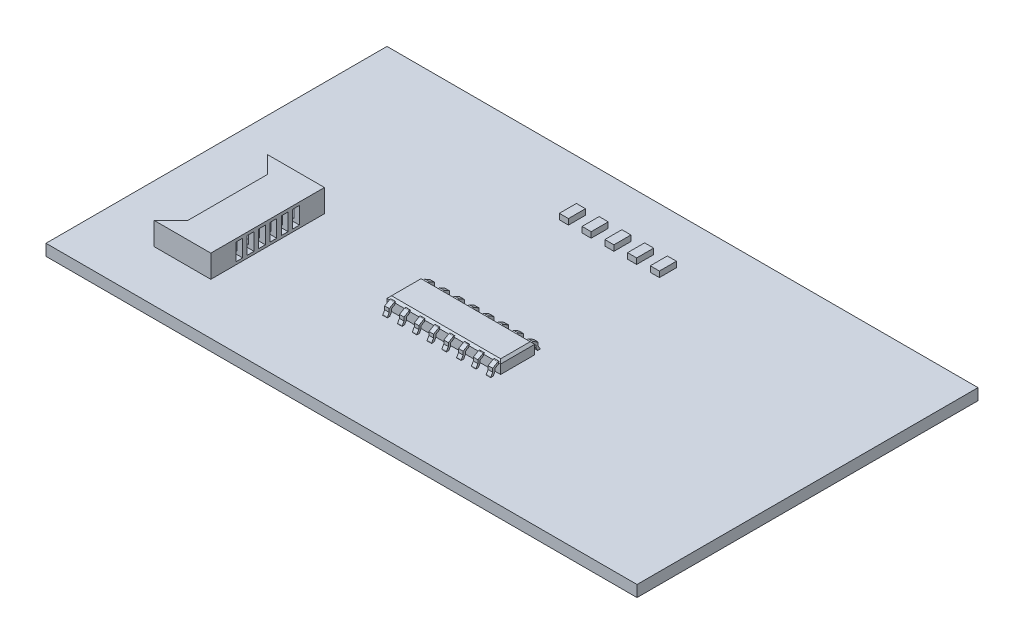
SolidWorks part; units mm, degrees
ref_plane "前视基准面" through (0, 0, 0) normal (0, 0, 1) x (1, 0, 0)
ref_plane "上视基准面" through (0, 0, 0) normal (0, 1, 0) x (1, 0, 0)
ref_plane "右视基准面" through (0, 0, 0) normal (1, 0, 0) x (0, 0, -1)
sketch "草图1" plane through (0, 0, 0) normal (0, 1, 0) x (1, 0, 0)
  line L1 (0, 0) -> (52, 0)
  line L2 (0, 0) -> (0, 30)
  line L3 (0, 30) -> (52, 30)
  line L4 (52, 0) -> (52, 30)
  dimension "D1" = 52
  dimension "D2" = 30
extrude "凸台-拉伸1" add sketch "草图1" along normal blind 1
sketch "草图2" plane through (0, 1, 0) normal (0, 1, 0) x (1, 0, 0)
  line L0 (0, 0) -> (52, 0) construction
  line L1 (5, 4.5) -> (10, 4.5)
  line L2 (5, 4.5) -> (5, 14.5)
  line L3 (5, 14.5) -> (10, 14.5)
  line L4 (10, 4.5) -> (10, 14.5)
  line L5 (0, 30) -> (0, 0) construction
  dimension "D1" = 5
  dimension "D2" = 10
  dimension "D3" = 14.5
  dimension "D4" = 5
extrude "凸台-拉伸2" add sketch "草图2" along normal blind 2
sketch "草图3" plane through (0, 3, 0) normal (0, 1, 0) x (1, 0, 0)
  line L0 (5, 14.5) -> (6.5, 13)
  line L1 (6.5, 13) -> (6.5, 6)
  line L2 (6.5, 6) -> (5, 4.5)
  line L3 (5, 4.5) -> (5, 14.5)
  dimension "D1" = 45
  dimension "D2" = 45
  dimension "D3" = 1.5
sketch "草图4" plane through (5, 0, 0) normal (-1, 0, 0) x (0, 0, 1)
  line L0 (-14.5, 2) -> (-4.5, 2) construction
  line L1 (-13.5, 1.5) -> (-5.5, 1.5)
  line L2 (-13.5, 1.5) -> (-13.5, 2.5)
  line L3 (-13.5, 2.5) -> (-5.5, 2.5)
  line L4 (-5.5, 1.5) -> (-5.5, 2.5)
  line L5 (-13.5, 1.5) -> (-5.5, 2.5) construction
  line L6 (-13.5, 2.5) -> (-5.5, 1.5) construction
  line L7 (-14.5, 3) -> (-14.5, 1) construction
  line L8 (-4.5, 3) -> (-4.5, 1) construction
  line L9 (-9.5, 3) -> (-9.5, 1) construction
  line L10 (-13, 3) -> (-6, 3) construction
  line L11 (-14.5, 1) -> (-4.5, 1) construction
  point P0 (-9.5, 2)
  point P18 (-9.5, 2)
  dimension "D1" = 8
  dimension "D2" = 1
extrude "切除-拉伸1" cut sketch "草图4" against normal blind 4.5
extrude "切除-拉伸2" cut sketch "草图3" against normal blind 1.5 contours L1 L2 L3 L0
sketch "草图5" plane through (5, 0, 0) normal (-1, 0, 0) x (0, 0, 1)
  line L0 (-11.3, 2.7352) -> (-11.3, 1.2352)
  line L1 (-12.3, 2.7352) -> (-11.7, 2.7352)
  line L2 (-12.3, 2.7352) -> (-12.3, 1.2352)
  line L3 (-12.3, 1.2352) -> (-11.7, 1.2352)
  line L4 (-11.7, 2.7352) -> (-11.7, 1.2352)
  line L5 (-12.3, 2.7352) -> (-11.7, 1.2352) construction
  line L6 (-12.3, 1.2352) -> (-11.7, 2.7352) construction
  line L7 (-11.3, 2.7352) -> (-10.7, 2.7352)
  line L8 (-10.7, 2.7352) -> (-10.7, 1.2352)
  line L9 (-11.3, 1.2352) -> (-10.7, 1.2352)
  line L10 (-10.3, 2.7352) -> (-10.3, 1.2352)
  line L11 (-10.3, 2.7352) -> (-9.7, 2.7352)
  line L12 (-9.7, 2.7352) -> (-9.7, 1.2352)
  line L13 (-10.3, 1.2352) -> (-9.7, 1.2352)
  line L14 (-9.3, 2.7352) -> (-9.3, 1.2352)
  line L15 (-9.3, 2.7352) -> (-8.7, 2.7352)
  line L16 (-8.7, 2.7352) -> (-8.7, 1.2352)
  line L17 (-9.3, 1.2352) -> (-8.7, 1.2352)
  line L18 (-8.3, 2.7352) -> (-8.3, 1.2352)
  line L19 (-8.3, 2.7352) -> (-7.7, 2.7352)
  line L20 (-7.7, 2.7352) -> (-7.7, 1.2352)
  line L21 (-8.3, 1.2352) -> (-7.7, 1.2352)
  line L22 (-7.3, 2.7352) -> (-7.3, 1.2352)
  line L23 (-7.3, 2.7352) -> (-6.7, 2.7352)
  line L24 (-6.7, 2.7352) -> (-6.7, 1.2352)
  line L25 (-7.3, 1.2352) -> (-6.7, 1.2352)
  line L26 (-12.3, 1.9852) -> (-6.7, 1.9852) construction
  line L27 (-9.5, 2.7352) -> (-9.5, 1.2352) construction
  line L28 (-9.5, 3) -> (-9.5, 1) construction
  line L29 (-13, 3) -> (-6, 3) construction
  line L30 (-14.5, 1) -> (-4.5, 1) construction
  point P0 (-12, 1.9852)
  point P31 (-9.5, 1.9852)
  dimension "D1" = 0.6
  dimension "D2" = 1.5
  dimension "D3" = 6
extrude "切除-拉伸3" cut sketch "草图5" against normal blind 6
sketch "草图6" plane through (0, 1, 0) normal (0, 1, 0) x (1, 0, 0)
  line L0 (0, 30) -> (0, 0) construction
  line L1 (20, 13) -> (30, 13)
  line L2 (20, 13) -> (20, 10)
  line L3 (20, 10) -> (30, 10)
  line L4 (30, 13) -> (30, 10)
  line L5 (20, 13) -> (30, 10) construction
  line L6 (20, 10) -> (30, 13) construction
  line L7 (0, 0) -> (52, 0) construction
  point P0 (25, 11.5)
  dimension "D1" = 10
  dimension "D2" = 3
  dimension "D3" = 20
  dimension "D4" = 10
extrude "凸台-拉伸3" add sketch "草图6" along normal blind 1
chamfer "倒角1" distance 0.2 angle 45 4 edges at (30, 2, -11.5) (25, 2, -13) (20, 2, -11.5) (25, 2, -10)
ref_plane "基准面1" through (20.5, 0, 0) normal (-1, 0, 0) x (0, 0, 1)
sketch "草图7" plane through (20.5, 0, 0) normal (-1, 0, 0) x (0, 0, 1)
  line L0 (-10, 1.8) -> (-9.6, 1.5691) construction
  line L1 (-10, 1.8) -> (-10, 1) construction
  line L2 (-9.6, 1.5691) -> (-9.6, 1.3) construction
  line L3 (-9.6, 1.3) -> (-9.4268, 1) construction
  line L4 (-14.5, 1) -> (-4.5, 1) construction
  line L5 (-9.95, 1.8866) -> (-9.5, 1.6268)
  line L6 (-9.5, 1.6268) -> (-9.5, 1.3268)
  line L7 (-9.5, 1.3268) -> (-9.3402, 1.05)
  line L8 (-10.05, 1.7134) -> (-9.7, 1.5113)
  line L9 (-9.7, 1.5113) -> (-9.7, 1.2732)
  line L10 (-9.7, 1.2732) -> (-9.5134, 0.95)
  arc A0 (-9.95, 1.8866) -> (-10.05, 1.7134) centre (-10, 1.8) ccw
  arc A1 (-9.3402, 1.05) -> (-9.5134, 0.95) centre (-9.4268, 1) cw
  point P16 (0, 0)
  point P17 (-10, 1.4)
  point P18 (0, 0)
  dimension "D1" = 60
  dimension "D2" = 60
  dimension "D3" = 0.3
  dimension "D6" = 0.4
  dimension "D4" = 0.1
  dimension "D5" = 0.1
extrude "凸台-拉伸4" add sketch "草图7" along normal blind 0.2 and the other way blind 0.2 separate body
pattern_linear "阵列(线性)1" count 8 spacing 1.3 along (1, 0, 0) of bodies 112
ref_plane "基准面2" through (0, 0, -11.5) normal (0, 0, 1) x (1, 0, 0)
mirror "镜向1" about plane through (0, 0, -11.5) normal (0, 0, 1) of bodies 112 113 114 115 116 117 118 119
sketch "草图8" plane through (0, 1, 0) normal (0, 1, 0) x (1, 0, 0)
  line L1 (20.8001, 25.866) -> (21.6001, 25.866)
  line L2 (20.8001, 25.866) -> (20.8001, 24.366)
  line L3 (20.8001, 24.366) -> (21.6001, 24.366)
  line L4 (21.6001, 25.866) -> (21.6001, 24.366)
  line L5 (20.8001, 25.866) -> (21.6001, 24.366) construction
  line L6 (20.8001, 24.366) -> (21.6001, 25.866) construction
  point P0 (21.2001, 25.116)
  dimension "D1" = 0.8
  dimension "D2" = 1.5
extrude "凸台-拉伸5" add sketch "草图8" along normal blind 0.5 separate body
pattern_linear "阵列(线性)2" count 5 spacing 2 along (1, 0, 0) of bodies 128
